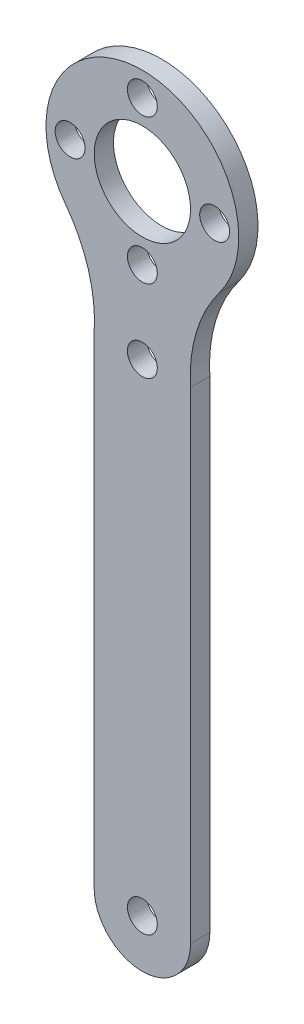
SolidWorks part; units mm, degrees
ref_plane "前视基准面" through (0, 0, 0) normal (0, 0, 1) x (1, 0, 0)
ref_plane "上视基准面" through (0, 0, 0) normal (0, 1, 0) x (1, 0, 0)
ref_plane "右视基准面" through (0, 0, 0) normal (1, 0, 0) x (0, 0, -1)
sketch "草图1" plane through (0, 0, 0) normal (0, 0, 1) x (1, 0, 0)
  line L0 (0, -25) -> (0, 25) construction
  line L1 (-5, -25) -> (-5, 25)
  line L2 (5, -25) -> (5, 25)
  arc A0 (-5, -25) -> (5, -25) centre (0, -25) ccw
  arc A1 (5, 25) -> (-5, 25) centre (0, 25) ccw
  circle A2 centre (0, 25) radius 1.55
  circle A3 centre (0, -25) radius 1.55
  circle A4 centre (0, 41) radius 10
  circle A5 centre (0, 41) radius 5
  circle A6 centre (0, 41) radius 7.5 construction
  circle A7 centre (0, 48.5) radius 1.55
  circle A8 centre (7.5, 41) radius 1.55
  circle A9 centre (0, 33.5) radius 1.55
  circle A10 centre (-7.5, 41) radius 1.55
  arc A11 (-5, 25) -> (-7.9877, 34.9837) centre (-19.9693, 25.9592) ccw
  arc A12 (5, 25) -> (7.9877, 34.9837) centre (19.9693, 25.9592) cw
  point P2 (0, 0)
  point P27 (0, 41)
  dimension "D3" = 3.1
  dimension "D4" = 3.1
  dimension "D5" = 20
  dimension "D7" = 10
  dimension "D8" = 15
  dimension "D9" = 3.1
  dimension "D11" = 15
  dimension "D12" = 15
  dimension "D1" = 50
  dimension "D2" = 10
  dimension "D6" = 16
  dimension "D10" = 4
extrude "凸台-拉伸1" add sketch "草图1" along normal blind 2 contours A4 A10 A9 A8 A7 A5 | L2 A1 L1 A0 A3 A2 | A1 A12 A4 | A11 A1 A4
